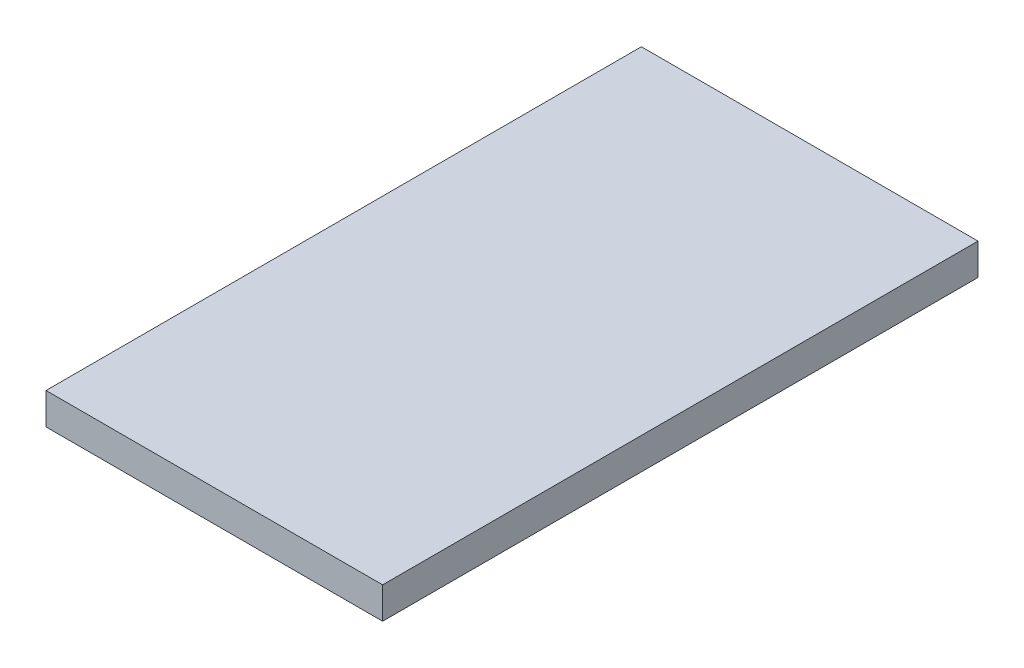
SolidWorks part; units mm, degrees
material "Plywood"
ref_plane "Front Plane" through (0, 0, 0) normal (0, 0, 1) x (1, 0, 0)
ref_plane "Top Plane" through (0, 0, 0) normal (0, 1, 0) x (1, 0, 0)
ref_plane "Right Plane" through (0, 0, 0) normal (1, 0, 0) x (0, 0, -1)
sketch "Sketch1" plane through (0, 0, 0) normal (0, 1, 0) x (1, 0, 0)
  line L1 (-73.1886, 227.1433) -> (130.0114, 227.1433)
  line L2 (-73.1886, 227.1433) -> (-73.1886, -132.2667)
  line L3 (-73.1886, -132.2667) -> (130.0114, -132.2667)
  line L4 (130.0114, 227.1433) -> (130.0114, -132.2667)
  line L5 (-73.1886, 227.1433) -> (130.0114, -132.2667) construction
  line L6 (-73.1886, -132.2667) -> (130.0114, 227.1433) construction
  point P0 (28.4114, 47.4383)
extrude "Boss-Extrude1" add sketch "Sketch1" along normal blind 19.05 contours L2 L1 L4 L3
